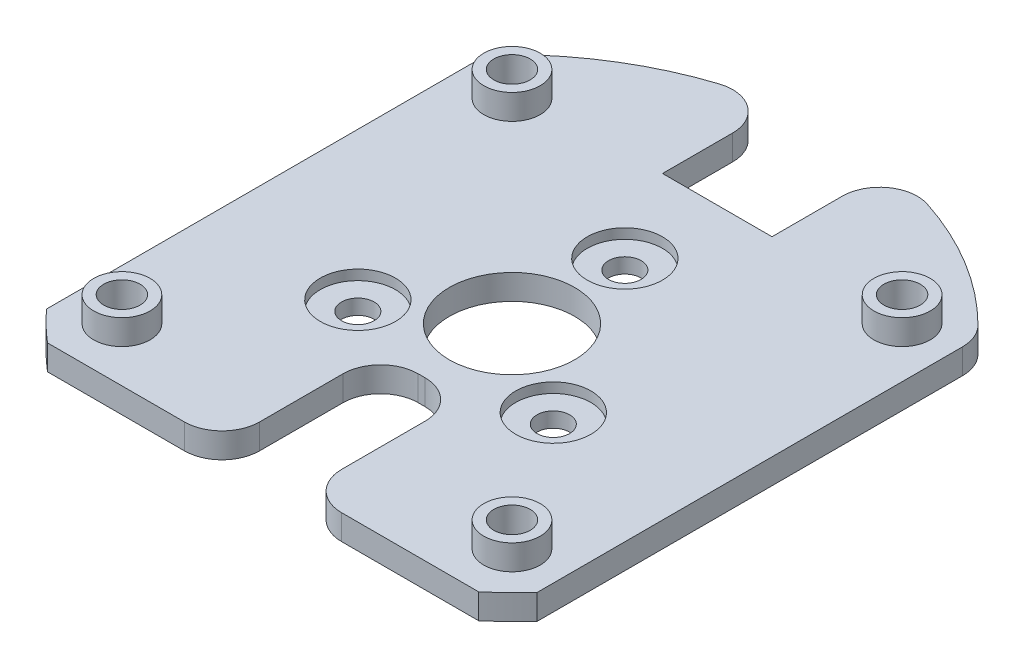
SolidWorks part; units mm, degrees
ref_plane "前视基准面" through (0, 0, 0) normal (0, 0, 1) x (1, 0, 0)
ref_plane "上视基准面" through (0, 0, 0) normal (0, 1, 0) x (1, 0, 0)
ref_plane "右视基准面" through (0, 0, 0) normal (1, 0, 0) x (0, 0, -1)
other "Configuration Table"
sketch "草图1" plane through (0, 0, 0) normal (0, 1, 0) x (1, 0, 0)
  line L3 (0, 0) -> (0, 29.2579) construction
  line L5 (0, 0) -> (6.9631, 0) construction
  line L6 (-19.5704, 15.5563) -> (-19.5704, -15.5563)
  line L7 (19.5704, 15.5563) -> (19.5704, -15.5563)
  line L8 (-19.5704, 15.5563) -> (-19.5704, 17.5563)
  line L9 (19.5704, 15.5563) -> (19.5704, 17.5563)
  line L10 (19.5704, -15.5563) -> (19.5704, -17.5563)
  line L11 (-19.5704, -15.5563) -> (-19.5704, -17.5563)
  circle A0 centre (0, 9) radius 1.3
  circle A1 centre (7.7942, -4.5) radius 1.3
  circle A2 centre (-7.7942, -4.5) radius 1.3
  circle A3 centre (0, 0) radius 5
  circle A5 centre (-15.5563, 15.5563) radius 1.45
  circle A17 centre (15.5563, 15.5563) radius 1.45
  circle A19 centre (15.5563, -15.5563) radius 1.45
  circle A21 centre (-15.5563, -15.5563) radius 1.45
  arc A39 (-19.5704, 17.5563) -> (0, 26.0785) centre (-0.2846, 0) cw
  arc A40 (19.5704, 17.5563) -> (0, 26.0785) centre (0.2846, 0) ccw
  arc A41 (19.5704, -17.5563) -> (0, -26.0785) centre (0.2846, 0) cw
  arc A42 (-19.5704, -17.5563) -> (0, -26.0785) centre (-0.2846, 0) ccw
  point P8 (0, 0)
  point P22 (0, 0)
  point P29 (0, 0)
  point P30 (0, 0)
  point P55 (0, 0)
  point P60 (0, 0)
  point P64 (0, 0)
  point P72 (0, 0)
  dimension "D1" = 3
  dimension "D2" = 4
extrude "凸台-拉伸1" add sketch "草图1" along normal blind 2
sketch "草图2" plane through (0, 2, 0) normal (0, 1, 0) x (1, 0, 0)
  circle A0 centre (0, 9) radius 3
  circle A1 centre (7.7942, -4.5) radius 3
  circle A2 centre (-7.7942, -4.5) radius 3
  point P9 (0, 0)
  dimension "D1" = 3
extrude "切除-拉伸1" cut sketch "草图2" against normal blind 0.8
sketch "草图4" plane through (0, 2, 0) normal (0, 1, 0) x (1, 0, 0)
  line L0 (-3.2742, -19.8551) -> (-3.2742, -7.206)
  line L1 (-4.3672, 26.4923) -> (4.3672, 26.4923)
  line L2 (-4.3672, 26.4923) -> (-4.3672, 16.3715)
  line L3 (-4.3672, 16.3715) -> (4.3672, 16.3715)
  line L4 (4.3672, 26.4923) -> (4.3672, 16.3715)
  line L5 (0, 16.3715) -> (0, 26.4923) construction
  line L6 (-4.3672, 21.4319) -> (4.3672, 21.4319) construction
  line L9 (3.2742, -7.206) -> (-3.2742, -7.206)
  line L11 (0, -7.206) -> (0, -28.5485) construction
  line L12 (2.5, -17.8772) -> (-2.5, -17.8772) construction
  line L13 (19.6117, -26.5068) -> (-19.6117, -26.5068)
  line L14 (19.6117, -26.5068) -> (19.6117, -19.8551)
  line L15 (19.6117, -19.8551) -> (3.2742, -19.8551)
  line L16 (-19.6117, -26.5068) -> (-19.6117, -19.8551)
  line L17 (0, -20.6869) -> (0, -26.5068) construction
  line L18 (19.6117, -23.181) -> (-19.6117, -23.181) construction
  line L19 (3.2742, -19.8551) -> (3.2742, -7.206)
  line L20 (-3.2742, -19.8551) -> (-19.6117, -19.8551)
  point P0 (0, 21.4319)
  point P4 (0, -23.181)
  point P5 (0, -17.8772)
extrude "切除-拉伸2" cut sketch "草图4" against normal through all
sketch "草图8" plane through (0, 2, 0) normal (0, 1, 0) x (1, 0, 0)
  circle A4 centre (-15.5563, 15.5563) radius 2.25
  circle A5 centre (15.5563, 15.5563) radius 2.25
  circle A6 centre (15.5563, -15.5563) radius 2.25
  circle A7 centre (-15.5563, -15.5563) radius 2.25
  circle A8 centre (-15.5563, 15.5563) radius 1.45
  circle A9 centre (15.5563, 15.5563) radius 1.45
  circle A10 centre (15.5563, -15.5563) radius 1.45
  circle A11 centre (-15.5563, -15.5563) radius 1.45
  point P11 (0, 0)
  point P12 (0, 0)
  point P20 (0, 0)
  dimension "D1" = 4
  dimension "D2" = 4
extrude "凸台-拉伸2" add sketch "草图8" along normal blind 2
sketch "草图7" plane through (0, 0, 0) normal (0, -1, 0) x (1, 0, 0)
  line L1 (-18.7324, 15.5563) -> (-17.1444, 12.8058)
  line L2 (-17.1444, 12.8058) -> (-13.9683, 12.8058)
  line L3 (-13.9683, 12.8058) -> (-12.3803, 15.5563)
  line L4 (-12.3803, 15.5563) -> (-13.9683, 18.3068)
  line L5 (-13.9683, 18.3068) -> (-17.1444, 18.3068)
  line L6 (-17.1444, 18.3068) -> (-18.7324, 15.5563)
  line L7 (12.3803, 15.5563) -> (13.9683, 12.8058)
  line L8 (13.9683, 12.8058) -> (17.1444, 12.8058)
  line L9 (17.1444, 12.8058) -> (18.7324, 15.5563)
  line L10 (18.7324, 15.5563) -> (17.1444, 18.3068)
  line L11 (17.1444, 18.3068) -> (13.9683, 18.3068)
  line L12 (13.9683, 18.3068) -> (12.3803, 15.5563)
  line L13 (-18.7324, -15.5563) -> (-17.1444, -18.3068)
  line L14 (-17.1444, -18.3068) -> (-13.9683, -18.3068)
  line L15 (-13.9683, -18.3068) -> (-12.3803, -15.5563)
  line L16 (-12.3803, -15.5563) -> (-13.9683, -12.8058)
  line L17 (-13.9683, -12.8058) -> (-17.1444, -12.8058)
  line L18 (-17.1444, -12.8058) -> (-18.7324, -15.5563)
  line L19 (12.3803, -15.5563) -> (13.9683, -18.3068)
  line L20 (13.9683, -18.3068) -> (17.1444, -18.3068)
  line L21 (17.1444, -18.3068) -> (18.7324, -15.5563)
  line L22 (18.7324, -15.5563) -> (17.1444, -12.8058)
  line L23 (17.1444, -12.8058) -> (13.9683, -12.8058)
  line L24 (13.9683, -12.8058) -> (12.3803, -15.5563)
  circle A4 centre (-15.5563, 15.5563) radius 2.7505 construction
  circle A5 centre (15.5563, 15.5563) radius 2.7505 construction
  circle A6 centre (-15.5563, -15.5563) radius 2.7505 construction
  circle A7 centre (15.5563, -15.5563) radius 2.7505 construction
extrude "切除-拉伸4" cut sketch "草图7" against normal blind 1
fillet "圆角3" radius 3 8 edges at (-3.2742, 1, 7.206) (3.2742, 1, 7.206) (3.2742, 1, 19.8551) (-3.2742, 1, 19.8551) (4.3672, 1, -25.7585) (-4.3672, 1, -25.7585) (19.5704, 1, -17.5563) (-19.5704, 1, -17.5563)
